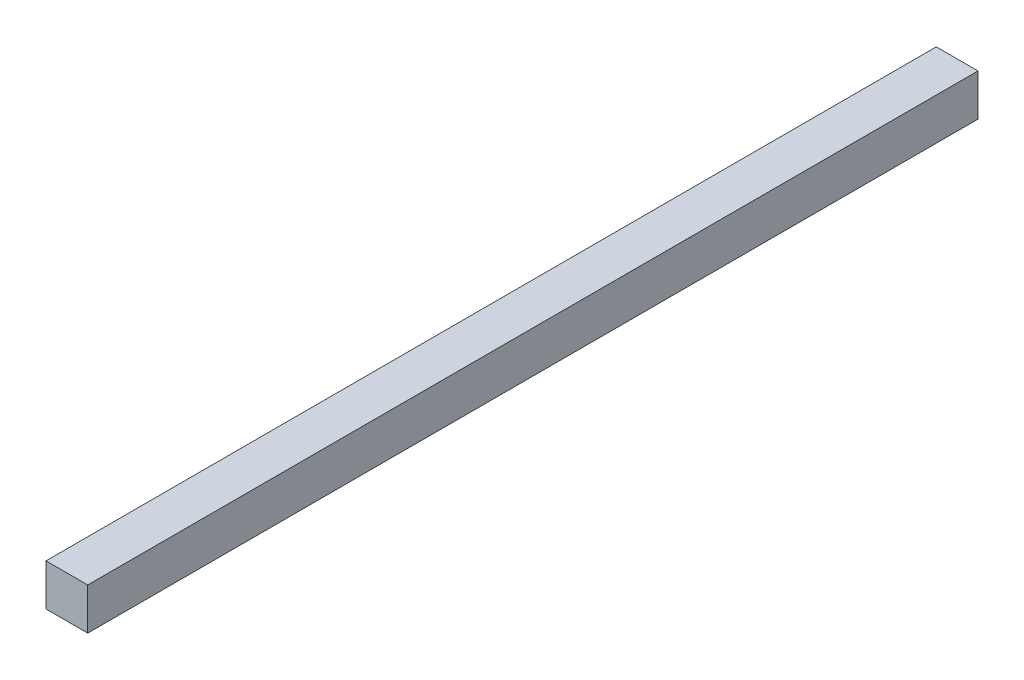
SolidWorks part; units mm, degrees
ref_plane "Front Plane" through (0, 0, 0) normal (0, 0, 1) x (1, 0, 0)
ref_plane "Top Plane" through (0, 0, 0) normal (0, 1, 0) x (1, 0, 0)
ref_plane "Right Plane" through (0, 0, 0) normal (1, 0, 0) x (0, 0, -1)
sketch "Sketch1" plane through (0, 0, 0) normal (0, 0, 1) x (1, 0, 0)
  line L0 (-25.4, 762) -> (25.4, 762) construction
  line L1 (-19.05, 711.2) -> (19.05, 711.2)
  line L2 (-19.05, 711.2) -> (-19.05, 673.1)
  line L3 (-19.05, 673.1) -> (19.05, 673.1)
  line L4 (19.05, 711.2) -> (19.05, 673.1)
  line L5 (-25.4, 762) -> (-25.4, 0) construction
  dimension "D1" = 38.1
  dimension "D2" = 38.1
  dimension "D3" = 50.8
  dimension "D4" = 6.35
extrude "Boss-Extrude1" add sketch "Sketch1" along normal blind 812.8
